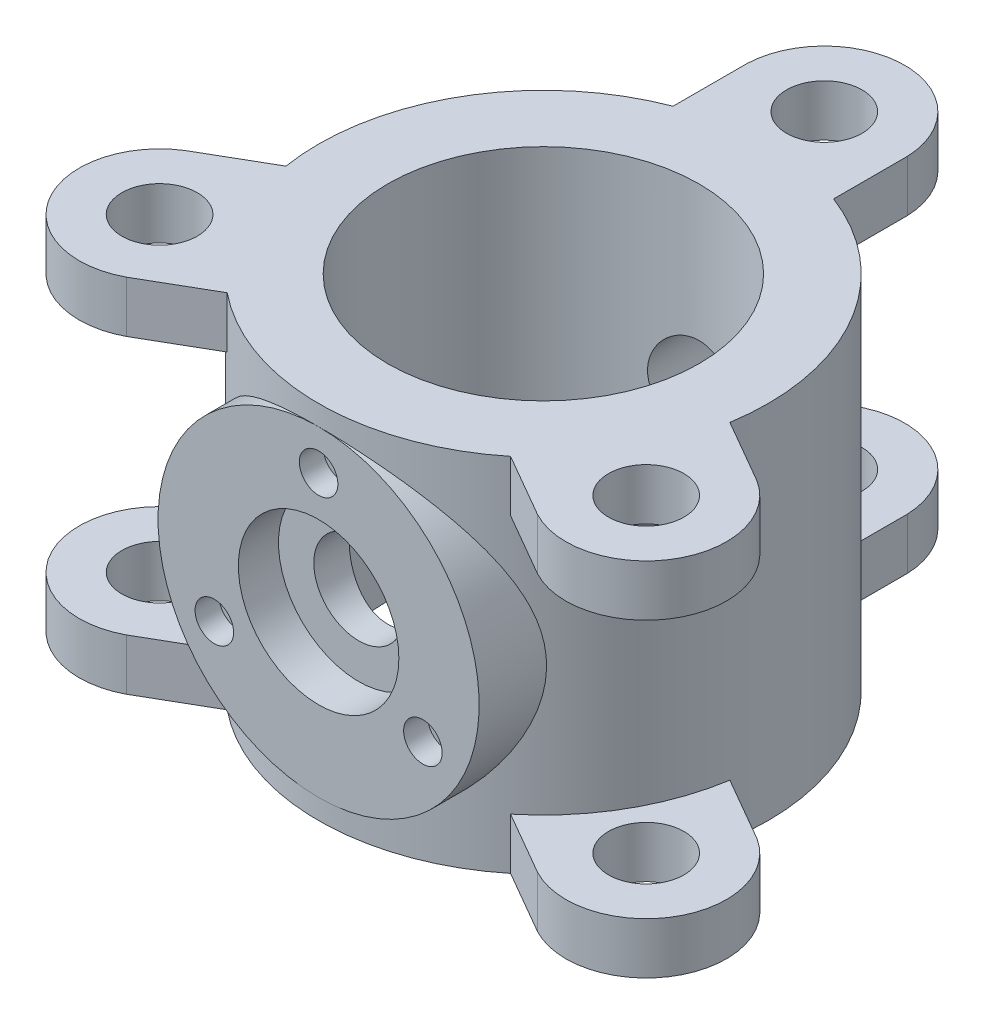
SolidWorks part; units mm, degrees
ref_plane "Front Plane" through (0, 0, 0) normal (0, 0, 1) x (1, 0, 0)
ref_plane "Top Plane" through (0, 0, 0) normal (0, 1, 0) x (1, 0, 0)
ref_plane "Right Plane" through (0, 0, 0) normal (1, 0, 0) x (0, 0, -1)
sketch "Sketch1" plane through (0, 0, 0) normal (0, 1, 0) x (1, 0, 0)
  line L0 (-989.6829, 0) -> (1118.4772, 0) construction
  line L1 (0, 580.4219) -> (0, -671.9337) construction
  circle A0 centre (0, 0) radius 97
  circle A1 centre (0, 0) radius 140
  dimension "D1" = 194
  dimension "D2" = 280
extrude "Boss-Extrude1" add sketch "Sketch1" along normal blind 225
sketch "Sketch5" plane through (0, 0, 0) normal (0, -1, 0) x (-1, 0, 0)
  line L0 (-204.8662, 0) -> (239.139, 0) construction
  line L1 (0, 257.5215) -> (0, -291.0592) construction
  line L4 (-50, 176.7951) -> (-50, 124.9678)
  line L5 (-50, 124.9678) -> (50, 124.9678)
  line L6 (50, 176.7951) -> (50, 124.9678)
  circle A0 centre (0, 175) radius 23.5
  arc A1 (50, 173.2049) -> (-50, 173.2049) centre (0, 175) ccw
  circle M4 centre (0, 0) radius 140
  dimension "D3" = 47
  dimension "D1" = 124.9678
  dimension "D2" = 50
  dimension "D4" = 175
  dimension "D5" = 50
extrude "Boss-Extrude2" add sketch "Sketch5" against normal blind 32 contours L6 A1 L4 A0 M4
pattern_circular "CirPattern1" count 3 over 360 about axis through (0, 0, 0) along (0, 1, 0) of "Boss-Extrude2"
ref_plane "Plane1" through (0, 112.5, 0) normal (0, -1, 0) x (-1, 0, 0)
mirror "Mirror1" about plane through (0, 112.5, 0) normal (0, -1, 0) of "CirPattern1", "Boss-Extrude2"
ref_plane "Plane2" through (0, 0, 140) normal (0, 0, 1) x (1, 0, 0)
sketch "Sketch6" plane through (0, 0, 140) normal (0, 0, 1) x (1, 0, 0)
  line L0 (0, 266.8557) -> (0, -67.3067) construction
  line L1 (-259.6947, 112.5) -> (300.2278, 112.5) construction
  line L2 (-88.2475, 0) -> (88.2475, 0) construction
  circle A2 centre (0, 112.5) radius 100
  dimension "D1" = 200
  dimension "D5" = 112.5
extrude "Boss-Extrude3" add sketch "Sketch6" against normal up to next
sketch "Sketch7" plane through (0, 0, 140) normal (0, 0, 1) x (1, 0, 0)
  circle A0 centre (0, 112.5) radius 50
  dimension "D1" = 100
extrude "Cut-Extrude1" cut sketch "Sketch7" against normal blind 25
sketch "Sketch8" plane through (0, 0, 115) normal (0, 0, 1) x (1, 0, 0)
  circle A0 centre (0, 112.5) radius 28
  dimension "D1" = 56
extrude "Cut-Extrude2" cut sketch "Sketch8" against normal through all
sketch "Sketch9" plane through (0, 0, 140) normal (0, 0, 1) x (1, 0, 0)
  line L0 (-200.7677, 112.5) -> (200.7677, 112.5) construction
  circle A0 centre (0, 187.5) radius 12
  dimension "D1" = 24
  dimension "D2" = 75
extrude "Cut-Extrude3" cut sketch "Sketch9" against normal blind 15
pattern_circular "CirPattern2" count 3 over 360 about axis through (0, 112.5, 0) along (0, 0, 1) of "Cut-Extrude3"
